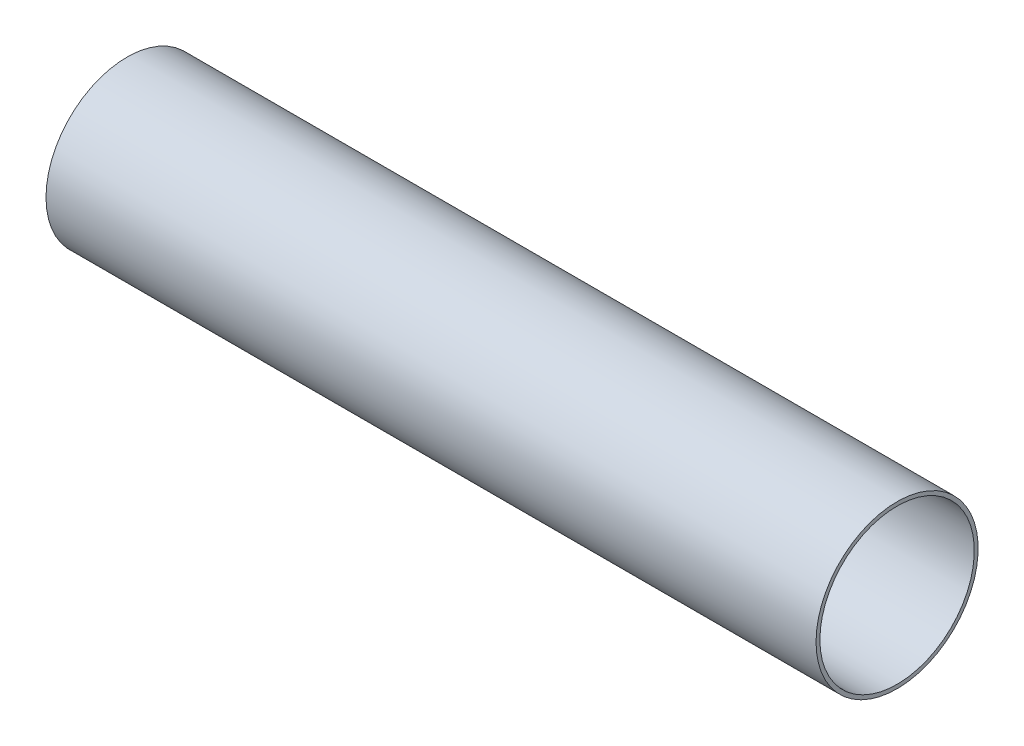
SolidWorks part; units mm, degrees
material "6061-T6 (SS)"
ref_plane "Front Plane" through (0, 0, 0) normal (0, 0, 1) x (1, 0, 0)
ref_plane "Top Plane" through (0, 0, 0) normal (0, 1, 0) x (1, 0, 0)
ref_plane "Right Plane" through (0, 0, 0) normal (1, 0, 0) x (0, 0, -1)
sketch "Sketch1" plane through (0, 0, 0) normal (1, 0, 0) x (0, 0, -1)
  circle A0 centre (0, 0) radius 101.6
  circle A1 centre (0, 0) radius 96.774
  dimension "D1" = 203.2
  dimension "D2" = 4.826
extrude "Boss-Extrude1" add sketch "Sketch1" along normal blind 965.2
